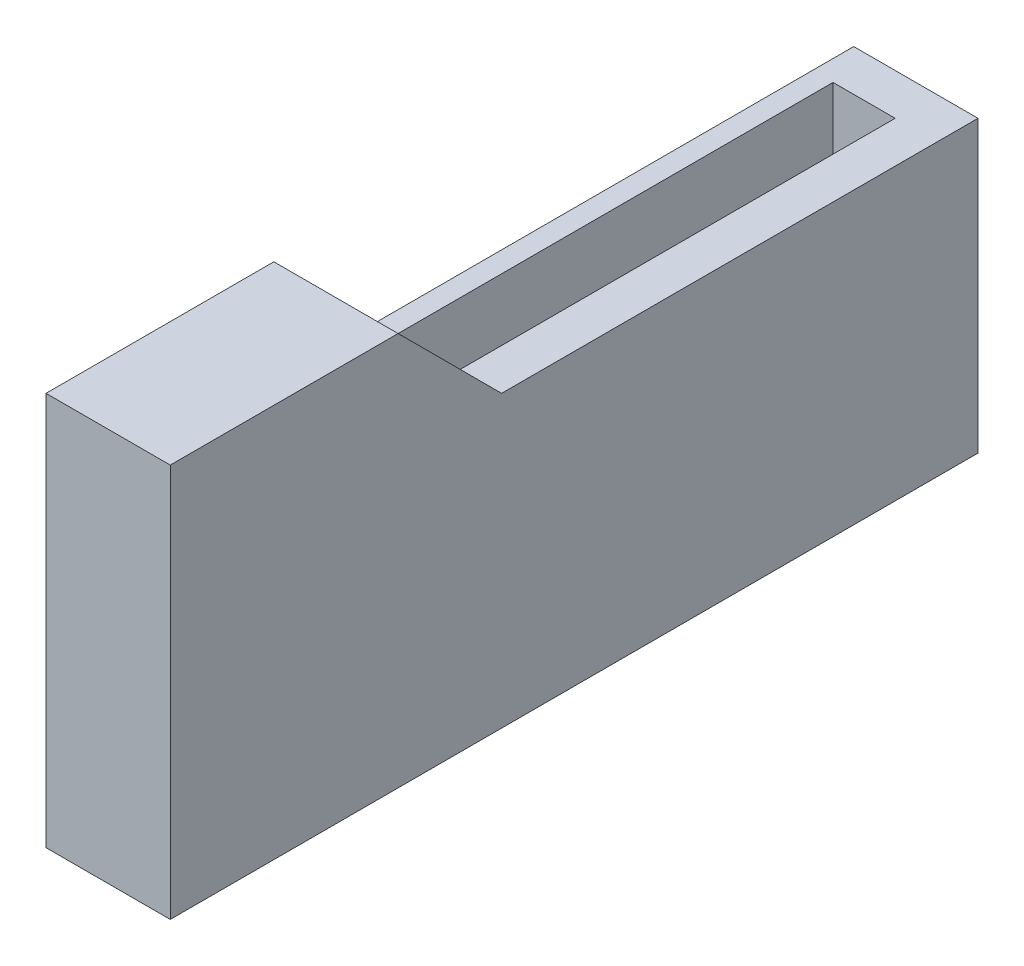
SolidWorks part; units mm, degrees
ref_plane "Спереди" through (0, 0, 0) normal (0, 0, 1) x (1, 0, 0)
ref_plane "Сверху" through (0, 0, 0) normal (0, 1, 0) x (1, 0, 0)
ref_plane "Справа" through (0, 0, 0) normal (1, 0, 0) x (0, 0, -1)
sketch "Эскиз1" plane through (0, 0, 0) normal (0, 1, 0) x (1, 0, 0)
  line L0 (-1.5, -10.5) -> (-1.5, -26.5)
  line L1 (1.5, -10.5) -> (-1.5, -10.5)
  line L2 (1.5, -10.5) -> (1.5, 10.5)
  line L3 (1.5, 10.5) -> (-1.5, 10.5)
  line L4 (-1.5, -10.5) -> (-1.5, -5.3571)
  line L5 (1.5, -10.5) -> (-1.5, 10.5) construction
  line L6 (1.5, 10.5) -> (-1.5, -10.5) construction
  line L7 (-1.5, -5.3571) -> (-1.5, 5.3571)
  line L9 (-1.5, 12.5) -> (3.5, 12.5)
  line L10 (3.5, -12.5) -> (3.5, 12.5)
  line L11 (-3.5, -12.5) -> (3.5, 12.5) construction
  line L12 (-3.5, 12.5) -> (3.5, -12.5) construction
  line L13 (-1.5, 5.3571) -> (-1.5, 10.5)
  line L14 (-2.5, -26.5) -> (-2.5, 12.5)
  line L15 (-3.5, -26.5) -> (3.5, -26.5)
  line L16 (3.5, -7.9733) -> (3.5, -26.5)
  line L17 (-1.5, -10.5) -> (1.5, -10.5)
  line L18 (-2.5, 12.5) -> (-1.5, 12.5)
  point P0 (0, 0)
  point P6 (0, 0)
  point P18 (-2.5, -26.5)
  dimension "D1" = 21
  dimension "D2" = 3
  dimension "D3" = 2
  dimension "D4" = 2
  dimension "D5" = 16
  dimension "D6" = 1
extrude "Бобышка-Вытянуть2" add sketch "Эскиз1" along normal blind 14
sketch "Эскиз3" plane through (0, 14, 0) normal (0, 1, 0) x (1, 0, 0)
  line L0 (3.5, 12.5) -> (3.5, -26.5) construction
  line L1 (-2.5, -26.5) -> (3.5, -26.5)
  line L2 (-2.5, -26.5) -> (-2.5, -10.5)
  line L3 (-2.5, -10.5) -> (3.5, -10.5)
  line L4 (3.5, -26.5) -> (3.5, -10.5)
  point P0 (1.5, -10.5)
extrude "Бобышка-Вытянуть3" add sketch "Эскиз3" along normal blind 5
chamfer "Фаска1" distance 5 angle 45 1 edges at (0.5, 19, 10.5)
